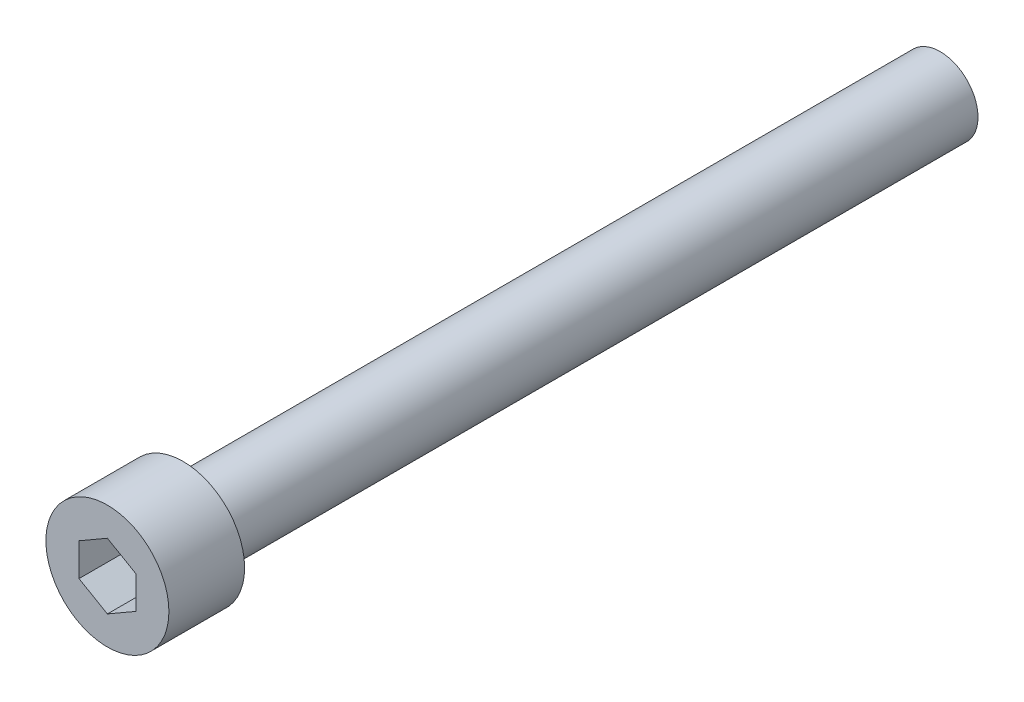
SolidWorks part; units mm, degrees
ref_plane "Płaszczyzna przednia" through (0, 0, 0) normal (0, 0, 1) x (1, 0, 0)
ref_plane "Płaszczyzna górna" through (0, 0, 0) normal (0, 1, 0) x (1, 0, 0)
ref_plane "Płaszczyzna prawa" through (0, 0, 0) normal (1, 0, 0) x (0, 0, -1)
sketch "Szkic1" plane through (0, 0, 0) normal (1, 0, 0) x (0, 0, -1)
  line L0 (0, 0) -> (30.4213, 0) construction
  line L1 (0, 0) -> (0, 6.5)
  line L2 (0, 6.5) -> (8, 6.5)
  line L3 (8, 6.5) -> (8, 4)
  line L4 (8, 4) -> (88, 4)
  line L5 (88, 4) -> (88, 0)
  line L6 (88, 0) -> (0, 0)
  dimension "D1" = 13
  dimension "D2" = 8
  dimension "D3" = 8
  dimension "D4" = 80
revolve "Obrót1" add sketch "Szkic1" angle 360 about L0
sketch "Szkic2" plane through (0, 0, 0) normal (0, 0, 1) x (1, 0, 0)
  line L1 (-3, -1.7321) -> (0, -3.4641)
  line L2 (0, -3.4641) -> (3, -1.7321)
  line L3 (3, -1.7321) -> (3, 1.7321)
  line L4 (3, 1.7321) -> (0, 3.4641)
  line L5 (0, 3.4641) -> (-3, 1.7321)
  line L6 (-3, 1.7321) -> (-3, -1.7321)
  circle A0 centre (0, 0) radius 3 construction
  dimension "D1" = 6
extrude "Wytnij-wyciągnięcie1" cut sketch "Szkic2" against normal blind 6
